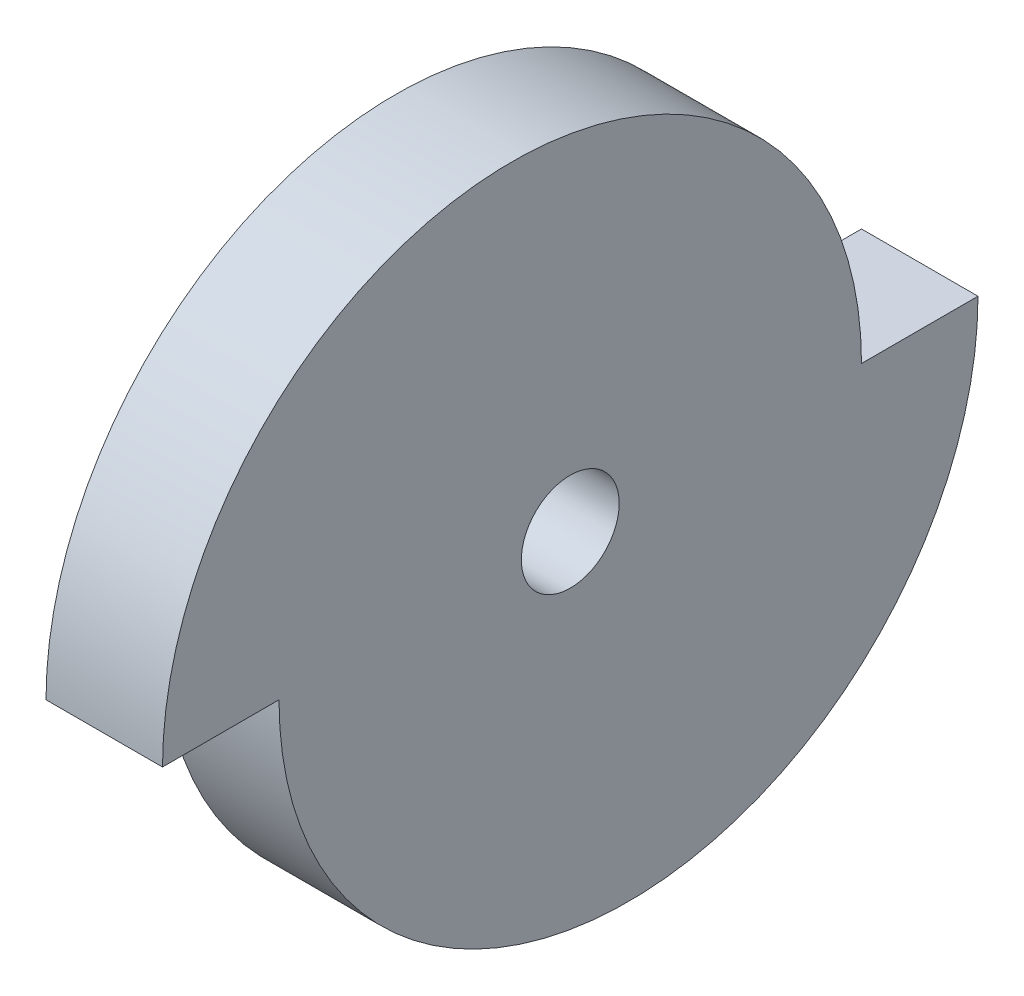
SolidWorks part; units mm, degrees
ref_plane "Front Plane" through (0, 0, 0) normal (0, 0, 1) x (1, 0, 0)
ref_plane "Top Plane" through (0, 0, 0) normal (0, 1, 0) x (1, 0, 0)
ref_plane "Right Plane" through (0, 0, 0) normal (1, 0, 0) x (0, 0, -1)
sketch "Sketch1" plane through (0, 0, 0) normal (1, 0, 0) x (0, 0, -1)
  line L3 (75.2867, 0) -> (80.2867, 0)
  line L4 (50.2867, 0) -> (45.2867, 0)
  arc A0 (75.2867, 0) -> (45.2867, 0) centre (60.2867, 0) ccw
  arc A1 (50.2867, 0) -> (80.2867, 0) centre (65.2867, 0) ccw
  dimension "D1" = 30
  dimension "D2" = 5
extrude "Boss-Extrude1" add sketch "Sketch1" along normal blind 5 contours A0 L4 A1 L3
sketch "Sketch2" plane through (5, 0, 0) normal (1, 0, 0) x (0, 0, -1)
  line L0 (45.2867, 0) -> (80.2867, 0) construction
  point P4 (62.7867, 0)
hole_wizard "M5x0.8 Tapped Hole1" positions "Sketch2" profile "Sketch3" tap size "M5x0.8" standard "ANSI Metric"
sketch "Sketch3" plane through (5, 0, -62.7867) normal (0, 1, 0) x (0, 0, -1)
  line L0 (0, 0) -> (0, 13.6618)
  line L1 (0, 13.6618) -> (2.1, 12.4)
  line L2 (2.1, 12.4) -> (2.1, 0)
  line L5 (2.1, 0) -> (0, 0)
  line L10 (0, 13.6618) -> (-2.1, 12.4) construction
  line L11 (0, -6.35) -> (0, 107.95) construction
  dimension "Tap Drill Dia." = 4.2
  dimension "Tap Drill Depth" = 12.4
  dimension "Drill Angle" = 118
cosmetic thread "Hole Thread1" parameters "D1"=10, "D2"=5
